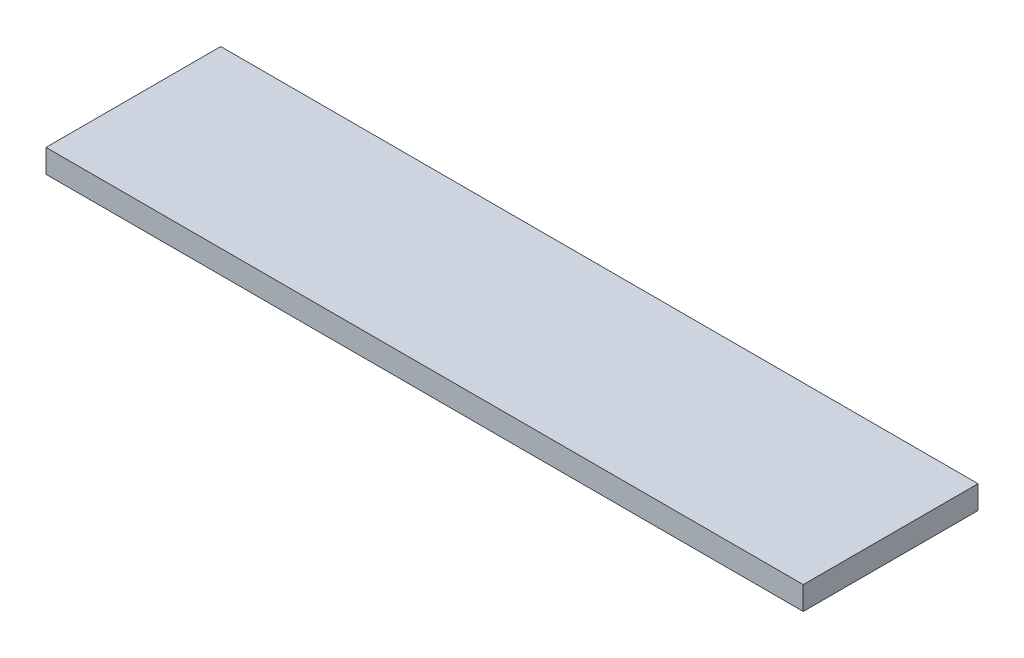
SolidWorks part; units mm, degrees
ref_plane "Front Plane" through (0, 0, 0) normal (0, 0, 1) x (1, 0, 0)
ref_plane "Top Plane" through (0, 0, 0) normal (0, 1, 0) x (1, 0, 0)
ref_plane "Right Plane" through (0, 0, 0) normal (1, 0, 0) x (0, 0, -1)
sketch "Sketch1" plane through (0, 0, 0) normal (0, 1, 0) x (1, 0, 0)
  line L1 (-162.5, 37.5) -> (162.5, 37.5)
  line L2 (-162.5, 37.5) -> (-162.5, -37.5)
  line L3 (-162.5, -37.5) -> (162.5, -37.5)
  line L4 (162.5, 37.5) -> (162.5, -37.5)
  line L5 (-162.5, 37.5) -> (162.5, -37.5) construction
  line L6 (-162.5, -37.5) -> (162.5, 37.5) construction
  point P0 (0, 0)
  dimension "D1" = 325
  dimension "D2" = 75
extrude "Boss-Extrude1" add sketch "Sketch1" along normal blind 10
sketch "Sketch2" plane through (0, 10, 0) normal (0, 1, 0) x (1, 0, 0)
  line L0 (-162.5, -25) -> (162.5, -25) construction
  line L1 (-162.5, 37.5) -> (-162.5, -37.5) construction
  line L2 (162.5, -37.5) -> (162.5, 37.5) construction
  line L3 (-162.5, -37.5) -> (162.5, -37.5) construction
  line L4 (-137.5, 37.5) -> (-137.5, -37.5) construction
  line L5 (162.5, 37.5) -> (-162.5, 37.5) construction
  line L6 (-137.5, -25) -> (-119.1854, -40.3678) construction
  dimension "D1" = 12.5
  dimension "D2" = 25
  dimension "D3" = 130
sketch3d "3DSketch2"
  line L0 (-137.5, 10, 25) -> (-137.5, 73.3283, 25)
ref_plane "Plane2" through (-69.1218, 0, 82.3761) normal (0.6428, 0, -0.766) x (-0.766, 0, -0.6428)
